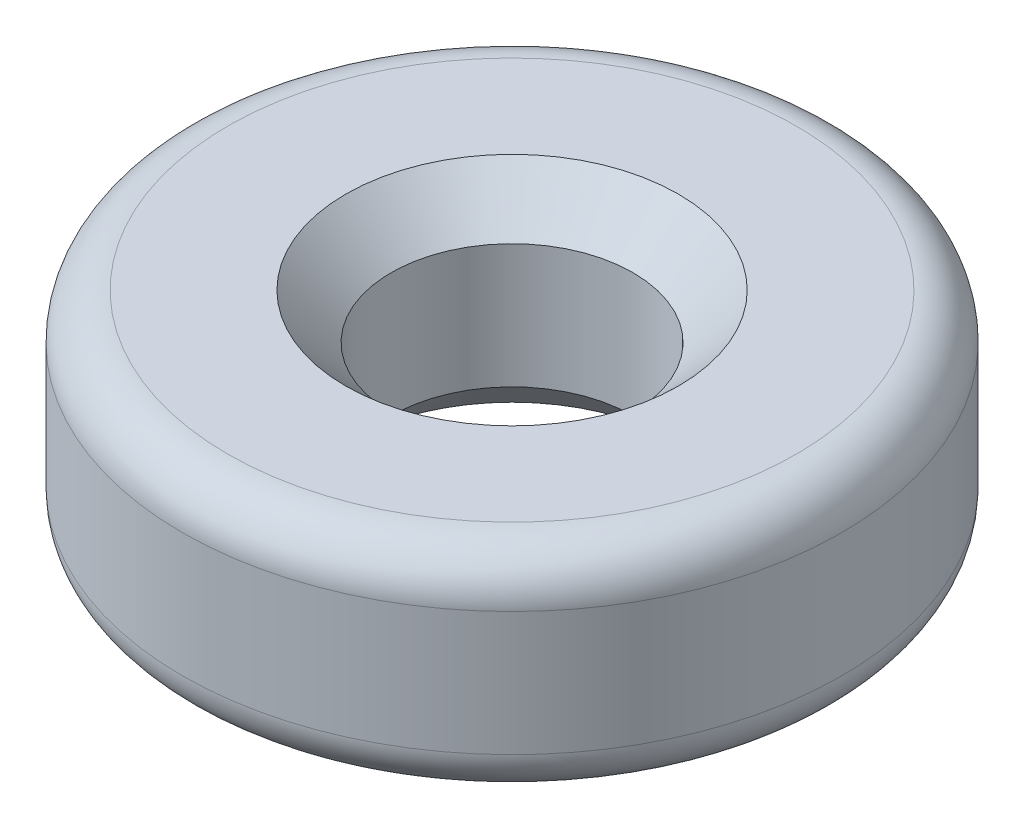
SolidWorks part; units mm, degrees
material "Tin Bearing Bronze"
ref_plane "Front Plane" through (0, 0, 0) normal (0, 0, 1) x (1, 0, 0)
ref_plane "Top Plane" through (0, 0, 0) normal (0, 1, 0) x (1, 0, 0)
ref_plane "Right Plane" through (0, 0, 0) normal (1, 0, 0) x (0, 0, -1)
sketch "Sketch1" plane through (0, 0, 0) normal (0, 1, 0) x (1, 0, 0)
  circle A0 centre (0, 0) radius 2.7686
  circle A1 centre (0, 0) radius 1.016
  dimension "D1" = 5.5372
  dimension "D2" = 2.032
extrude "Boss-Extrude1" add sketch "Sketch1" along normal blind 1.8034
fillet "Fillet1" radius 0.381 2 edges at (0, 0, 2.7686) (0, 1.8034, 2.7686)
chamfer "Chamfer1" distance 0.381 angle 45 2 edges at (0, 0, 1.016) (0, 1.8034, 1.016)
